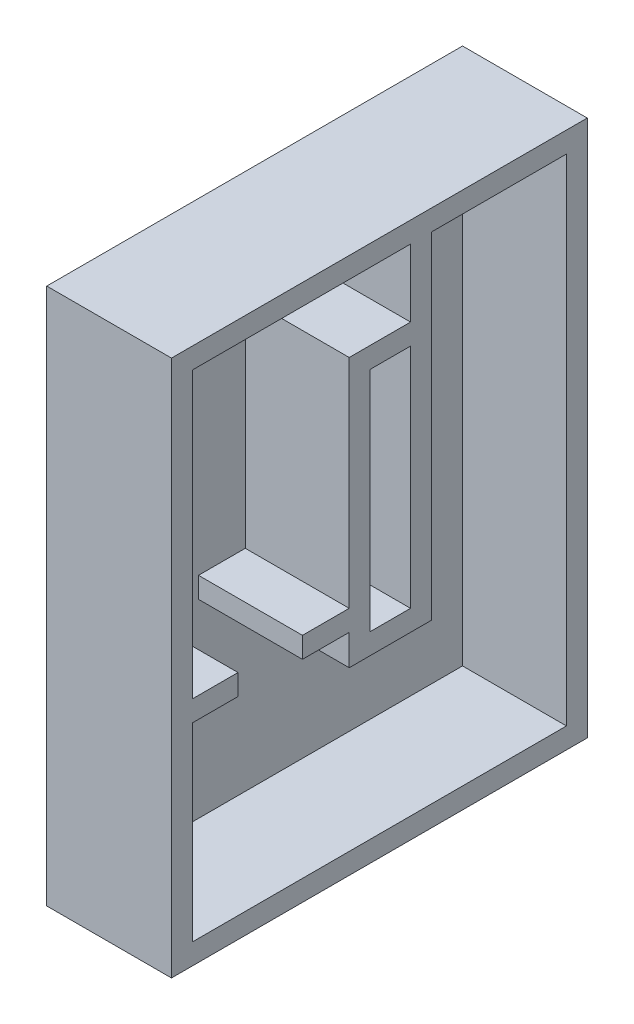
SolidWorks part; units mm, degrees
ref_plane "前视基准面" through (0, 0, 0) normal (0, 0, 1) x (1, 0, 0)
ref_plane "上视基准面" through (0, 0, 0) normal (0, 1, 0) x (1, 0, 0)
ref_plane "右视基准面" through (0, 0, 0) normal (1, 0, 0) x (0, 0, -1)
other "Configuration Table"
sketch "草图1" plane through (0, 0, 0) normal (1, 0, 0) x (0, 0, -1)
  line L1 (-20, 25.825) -> (20, 25.825)
  line L2 (-20, 25.825) -> (-20, -25.825)
  line L3 (-20, -25.825) -> (20, -25.825)
  line L4 (20, 25.825) -> (20, -25.825)
  line L5 (-20, 25.825) -> (20, -25.825) construction
  line L6 (-20, -25.825) -> (20, 25.825) construction
  point P0 (0, 0)
  dimension "D1" = 51.65
  dimension "D2" = 40
extrude "凸台-拉伸1" add sketch "草图1" along normal blind 12
shell "抽壳1" thickness 2
sketch "草图3" plane through (2, 0, 0) normal (1, 0, 0) x (0, 0, -1)
  line L19 (-2.9, 17.325) -> (3, 17.325)
  line L20 (-2.9, 17.325) -> (-2.9, -3.575)
  line L21 (-2.9, -8.525) -> (5, -8.525)
  line L22 (5, 17.175) -> (5, -8.525)
  line L23 (-3, 18.525) -> (-3, -3.475) construction
  line L24 (3.5, -8.725) -> (-4.5, -8.725) construction
  line L25 (8, 24.825) -> (8, -27.175) construction
  line L26 (18, 23.825) -> (-18, 23.825) construction
  line L27 (-18, 23.825) -> (-18, -23.825) construction
  line L28 (3, 23.825) -> (5, 23.825)
  line L29 (3, 23.825) -> (3, 17.325)
  line L31 (5, 23.825) -> (5, 17.175)
  line L32 (-0.9, 15.325) -> (3, 15.325)
  line L33 (-0.9, 15.325) -> (-0.9, -6.525)
  line L34 (-0.9, -6.525) -> (3, -6.525)
  line L35 (3, 15.325) -> (3, -6.525)
  line L36 (-18, -3.575) -> (-13.6, -3.575)
  line L37 (-18, -3.575) -> (-18, -5.575)
  line L38 (-18, -5.575) -> (-13.6, -5.575)
  line L39 (-13.6, -3.575) -> (-13.6, -5.575)
  line L40 (-18, -3.475) -> (-3, -3.475) construction
  line L41 (-7.4, -3.575) -> (-2.9, -3.575)
  line L42 (-7.4, -3.575) -> (-7.4, -5.575)
  line L43 (-7.4, -5.575) -> (-2.9, -5.575)
  line L45 (-7.5, -4.975) -> (-7.5, -3.475) construction
  line L46 (-13.5, -3.475) -> (-13.5, -4.975) construction
  line L48 (-2.9, -5.575) -> (-2.9, -8.525)
  dimension "D1" = 0.1
  dimension "D2" = 0.2
  dimension "D3" = 3
  dimension "D4" = 6.5
  dimension "D5" = 2
  dimension "D6" = 2
  dimension "D7" = 2
  dimension "D8" = 2
  dimension "D9" = 2
  dimension "D10" = 0.1
  dimension "D11" = 0.1
  dimension "D12" = 0.1
  dimension "D13" = 2
  dimension "D14" = 2
extrude "凸台-拉伸6" add sketch "草图3" along normal up to surface (10 mm away) up to face at (12, 0, 0)
